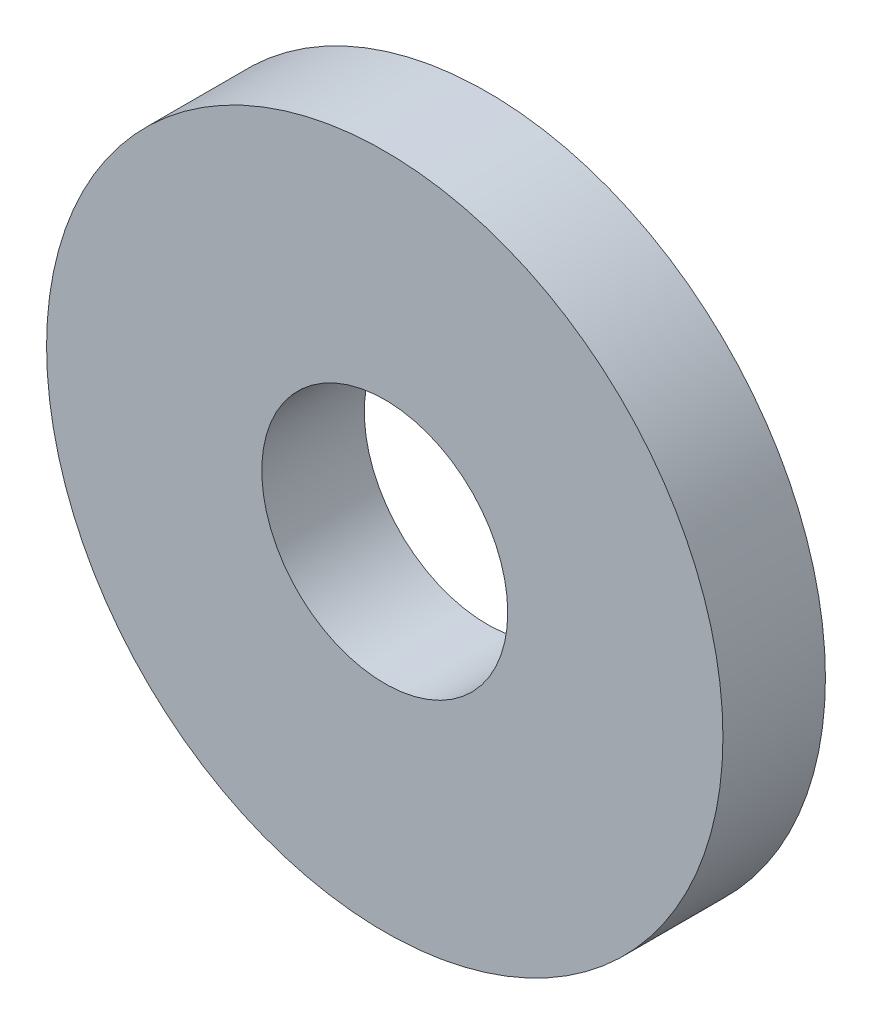
SolidWorks part; units mm, degrees
ref_plane "Front Plane" through (0, 0, 0) normal (0, 0, 1) x (1, 0, 0)
ref_plane "Top Plane" through (0, 0, 0) normal (0, 1, 0) x (1, 0, 0)
ref_plane "Right Plane" through (0, 0, 0) normal (1, 0, 0) x (0, 0, -1)
sketch "Sketch1" plane through (0, 0, 0) normal (0, 0, 1) x (1, 0, 0)
  circle A0 centre (-94.3013, 77.2301) radius 6
  circle A1 centre (-94.3013, 77.2301) radius 16.5
  dimension "D1" = 12
  dimension "D2" = 33
extrude "Boss-Extrude1" add sketch "Sketch1" along normal blind 5
